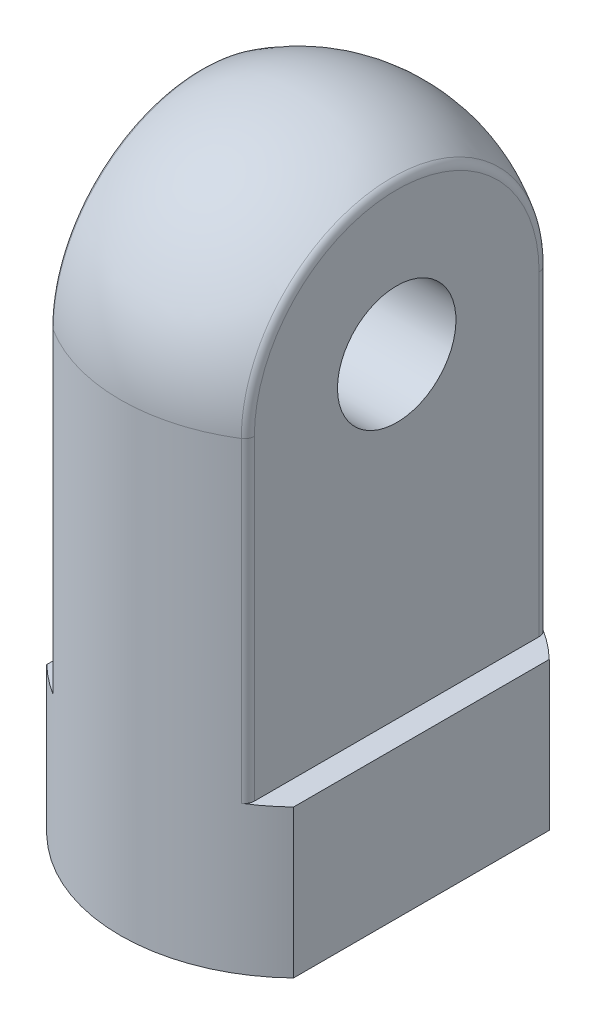
SolidWorks part; units mm, degrees
material "1060 合金"
ref_plane "前视基准面" through (0, 0, 0) normal (0, 0, 1) x (1, 0, 0)
ref_plane "上视基准面" through (0, 0, 0) normal (0, 1, 0) x (1, 0, 0)
ref_plane "右视基准面" through (0, 0, 0) normal (1, 0, 0) x (0, 0, -1)
sketch "草图1" plane through (0, 0, 0) normal (0, 1, 0) x (1, 0, 0)
  circle A0 centre (0, 0) radius 18
  dimension "D1" = 36
extrude "拉伸1" add sketch "草图1" along normal blind 65
fillet "圆角1" radius 18 1 edges at (0, 65, 18)
sketch "草图2" plane through (0, 0, 0) normal (0, 0, 1) x (1, 0, 0)
  line L0 (-12.5, 0) -> (-12.5, 15)
  line L1 (-18, 0) -> (18, 0) construction
  line L2 (-12.5, 15) -> (-10, 15)
  line L3 (-10, 15) -> (-10, 85.5185)
  line L4 (-10, 85.5185) -> (10, 85.5185)
  line L5 (0, 85.5185) -> (0, 0) construction
  line L6 (12.5, 0) -> (-12.5, 0)
  line L7 (10, 15) -> (10, 85.5185)
  line L8 (12.5, 15) -> (10, 15)
  line L9 (12.5, 0) -> (12.5, 15)
  dimension "D1" = 10
  dimension "D2" = 12.5
  dimension "D3" = 15
  dimension "D4" = 85.5185
extrude "拉伸2" cut sketch "草图2" against normal through all and the other way through all flip side to cut
sketch "草图3" plane through (-10, 0, 0) normal (-1, 0, 0) x (0, 0, 1)
  circle A0 centre (0, 47) radius 6
  arc A1 (14.9666, 47) -> (-14.9666, 47) centre (0, 47) ccw construction
  dimension "D1" = 12
extrude "拉伸3" cut sketch "草图3" against normal blind 80
hole_wizard "M12x1.75 螺纹孔1" positions "草图5" profile "草图4" tap size "M12x1.75" standard "Ansi Metric"
sketch "草图5" plane through (0, 0, 0) normal (0, -1, 0) x (1, 0, 0)
  point P0 (0, 0)
sketch "草图4" plane through (0, 0, 0) normal (1, 0, 0) x (0, 0, -1)
  line L0 (0, 0) -> (0, 35.8144)
  line L1 (0, 35.8144) -> (5.1, 32.75)
  line L2 (5.1, 32.75) -> (5.1, 0)
  line L5 (5.1, 0) -> (0, 0)
  line L10 (0, 35.8144) -> (-5.1, 32.75) construction
  line L11 (0, -6.35) -> (0, 107.95) construction
  dimension "螺纹孔钻头直径" = 10.2
  dimension "螺纹孔钻头深度" = 32.75
  dimension "导头角度" = 118
cosmetic thread "孔螺蚊线1" parameters "D1"=24, "D2"=12
fillet "圆角2" radius 1 6 edges at (10, 31, 14.9666) (10, 31, -14.9666) (-10, 31, -14.9666) (-10, 31, 14.9666) (10, 61.9666, 0) (-10, 61.9666, 0)
